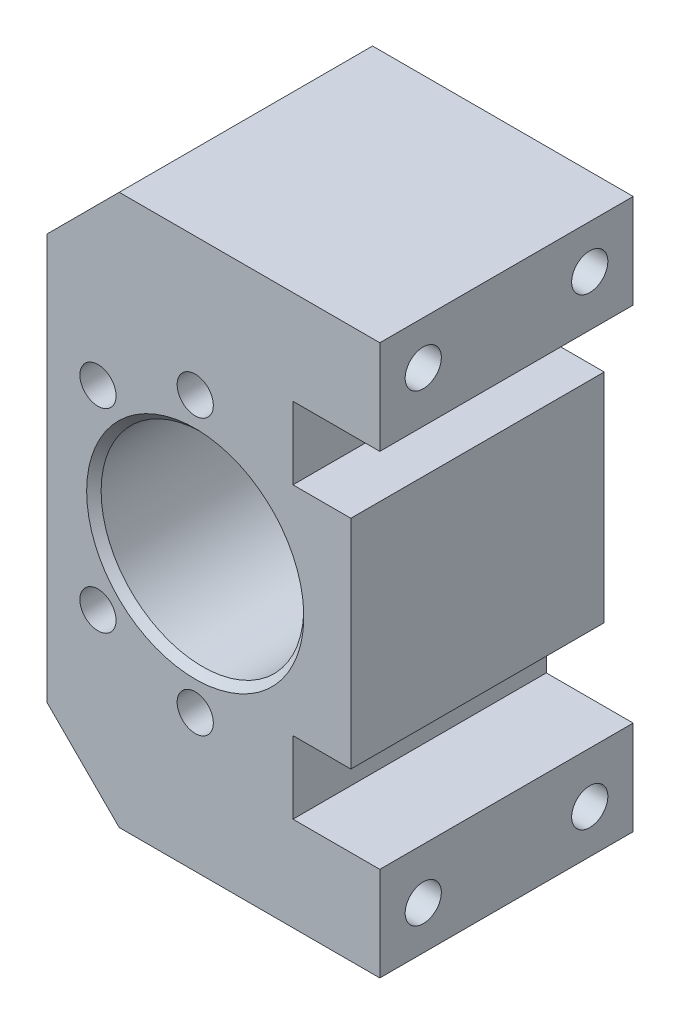
SolidWorks part; units mm, degrees
material "1.0037 (S235JR)"
ref_plane "Płaszczyzna przednia" through (0, 0, 0) normal (0, 0, 1) x (1, 0, 0)
ref_plane "Płaszczyzna górna" through (0, 0, 0) normal (0, 1, 0) x (1, 0, 0)
ref_plane "Płaszczyzna prawa" through (0, 0, 0) normal (1, 0, 0) x (0, 0, -1)
sketch "Szkic1" plane through (0, 0, 0) normal (0, 0, 1) x (1, 0, 0)
  line L0 (46, 38) -> (0, 38) construction
  line L1 (0, 0) -> (46, 0)
  line L2 (0, 0) -> (0, 76)
  line L3 (0, 76) -> (46, 76)
  line L4 (46, 0) -> (46, 76)
  circle A0 centre (20.5, 38) radius 14
  dimension "D3" = 28
  dimension "D1" = 46
  dimension "D2" = 76
  dimension "D4" = 20.5
extrude "Dodanie-wyciągnięcie1" add sketch "Szkic1" along normal blind 35
chamfer "Sfazowanie1" distance 1 angle 45 2 edges at (34.5, 38, 0) (34.5, 38, 35)
hole_wizard "Otwór gwintowany M6x1.01" positions "Szkic3" profile "Szkic2" tap size "M6x1.0" standard "Ansi Metric"
sketch "Szkic3" plane through (0, 0, 35) normal (0, 0, 1) x (1, 0, 0)
  circle A3 centre (7.065, 24.565) radius 3.3 construction
  circle A5 centre (7.065, 51.435) radius 3.3 construction
  circle A7 centre (20.5, 57) radius 3.3 construction
  circle A8 centre (20.5, 19) radius 3.3 construction
  point P0 (20.5, 57)
  point P2 (7.065, 51.435)
  point P5 (7.065, 24.565)
  point P7 (20.5, 19)
sketch "Szkic2" plane through (20.5, 57, 35) normal (1, 0, 0) x (0, -1, 0)
  line L0 (0, 0) -> (0, 18.5022)
  line L1 (0, 18.5022) -> (2.5, 17)
  line L2 (2.5, 17) -> (2.5, 0)
  line L5 (2.5, 0) -> (0, 0)
  line L10 (0, 18.5022) -> (-2.5, 17) construction
  line L11 (0, -6.35) -> (0, 107.95) construction
  dimension "Średnica wiertła gwintu" = 5
  dimension "Głębokość otworu gwintowanego" = 17
  dimension "Kąt wiertła" = 118
sketch "Szkic7" plane through (46, 0, 0) normal (1, 0, 0) x (0, 0, -1)
  line L8 (-6, 6) -> (-6, 70)
  line L9 (-6, 70) -> (-29, 70)
  line L10 (-29, 70) -> (-29, 6)
  line L11 (-29, 6) -> (-6, 6)
  line L12 (-6, 6) -> (-6, 70)
  line L13 (-6, 70) -> (-29, 70)
  line L14 (-29, 70) -> (-29, 6)
  line L15 (-29, 6) -> (-6, 6)
  dimension "D1" = 6
hole_wizard "Otwór gwintowany M6x1.03" positions "Szkic9" profile "Szkic8" tap size "M6x1.0" standard "Ansi Metric"
sketch "Szkic9" plane through (46, 0, 0) normal (1, 0, 0) x (0, 0, -1)
  point P0 (-29, 70)
  point P3 (-6, 70)
  point P6 (-6, 6)
  point P9 (-29, 6)
sketch "Szkic8" plane through (46, 70, 29) normal (0, 1, 0) x (0, 0, -1)
  line L0 (0, 0) -> (0, 18.5022)
  line L1 (0, 18.5022) -> (2.5, 17)
  line L2 (2.5, 17) -> (2.5, 0)
  line L5 (2.5, 0) -> (0, 0)
  line L10 (0, 18.5022) -> (-2.5, 17) construction
  line L11 (0, -6.35) -> (0, 107.95) construction
  dimension "Średnica wiertła gwintu" = 5
  dimension "Głębokość otworu gwintowanego" = 17
  dimension "Kąt wiertła" = 118
chamfer "Sfazowanie2" distance 10 angle 45 2 edges at (0, 0, 17.5) (0, 76, 17.5)
sketch "Szkic10" plane through (0, 0, 0) normal (0, 0, -1) x (-1, 0, 0)
  line L0 (-46, 13) -> (-46, 63)
  line L1 (-46, 0) -> (-46, 76) construction
  line L2 (-46, 63) -> (-34, 63)
  line L3 (-34, 63) -> (-34, 53)
  line L4 (-34, 53) -> (-42, 53)
  line L5 (-42, 53) -> (-42, 23)
  line L6 (-42, 23) -> (-34, 23)
  line L7 (-34, 23) -> (-34, 13)
  line L8 (-34, 13) -> (-46, 13)
  line L9 (0, 38) -> (-46, 38) construction
  line L10 (0, 66) -> (0, 10) construction
  dimension "D1" = 50
  dimension "D2" = 12
  dimension "D3" = 4
  dimension "D4" = 30
extrude "Wytnij-wyciągnięcie1" cut sketch "Szkic10" against normal through all
